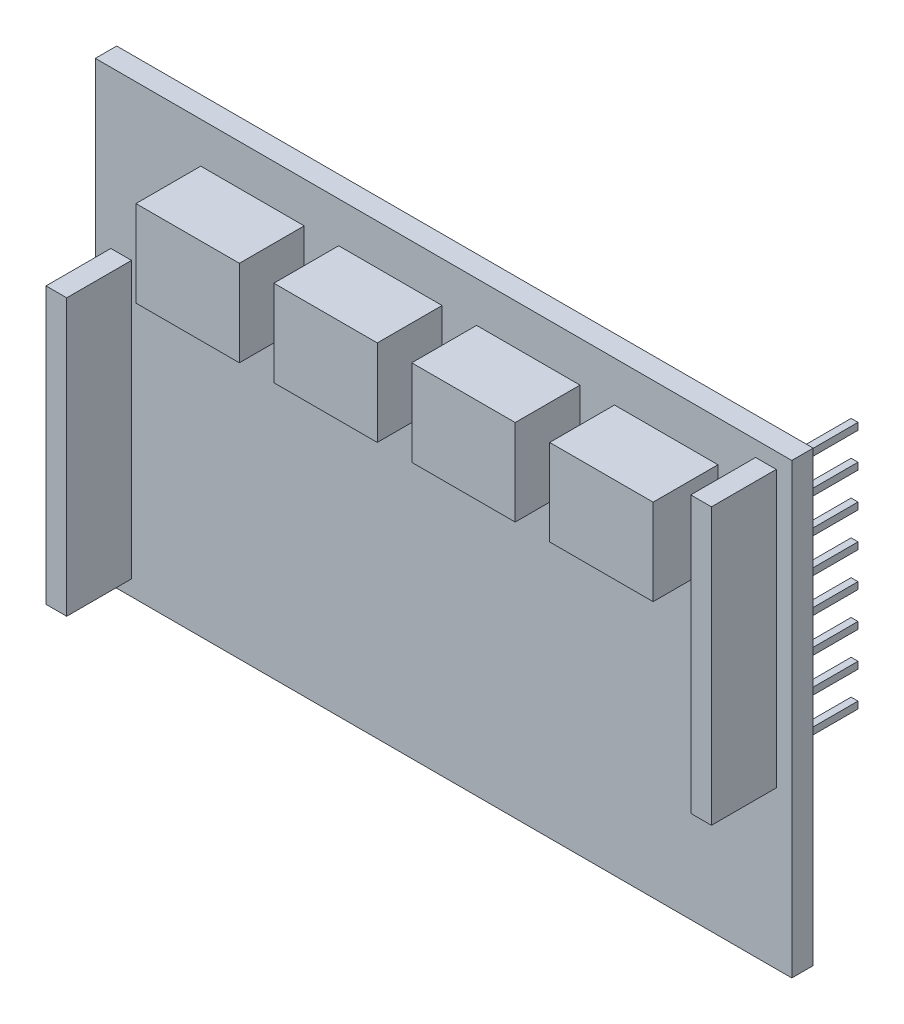
SolidWorks part; units mm, degrees
ref_plane "Front Plane" through (0, 0, 0) normal (0, 0, 1) x (1, 0, 0)
ref_plane "Top Plane" through (0, 0, 0) normal (0, 1, 0) x (1, 0, 0)
ref_plane "Right Plane" through (0, 0, 0) normal (1, 0, 0) x (0, 0, -1)
sketch "Sketch1" plane through (0, 0, 0) normal (0, 0, 1) x (1, 0, 0)
  line L0 (0, 0) -> (51.308, 0)
  line L1 (51.308, 0) -> (51.308, 33.02)
  line L2 (51.308, 33.02) -> (0, 33.02)
  line L3 (0, 33.02) -> (0, 0)
  dimension "D1" = 51.308
  dimension "D2" = 33.02
extrude "Boss-Extrude1" add sketch "Sketch1" along normal blind 1.5748
sketch "Sketch2" plane through (0, 0, 0) normal (0, 0, 1) x (1, 0, 0)
  line L0 (0, 33.02) -> (0, 0) construction
  line L1 (50.165, 31.877) -> (48.641, 31.877)
  line L2 (50.165, 31.877) -> (50.165, 11.557)
  line L3 (50.165, 11.557) -> (48.641, 11.557)
  line L4 (48.641, 31.877) -> (48.641, 11.557)
  line L5 (1.143, 1.143) -> (2.667, 1.143)
  line L6 (1.143, 1.143) -> (1.143, 21.463)
  line L7 (1.143, 21.463) -> (2.667, 21.463)
  line L8 (2.667, 1.143) -> (2.667, 21.463)
  line L9 (0, 0) -> (51.308, 0) construction
  line L10 (51.308, 0) -> (51.308, 33.02) construction
  line L11 (51.308, 33.02) -> (0, 33.02) construction
  dimension "D1" = 20.32
  dimension "D2" = 1.524
  dimension "D3" = 1.143
  dimension "D4" = 1.143
  dimension "D5" = 20.32
  dimension "D6" = 1.524
  dimension "D7" = 1.143
  dimension "D8" = 1.143
extrude "Boss-Extrude2" add sketch "Sketch2" along normal blind 6.35 contours L6 L5 L8 L7 | L2 L1 L4 L3
sketch "Sketch3" plane through (0, 0, 0) normal (0, 0, 1) x (1, 0, 0)
  line L1 (7.7673, 30.0262) -> (15.3873, 30.0262)
  line L2 (7.7673, 30.0262) -> (7.7673, 23.6762)
  line L3 (7.7673, 23.6762) -> (15.3873, 23.6762)
  line L4 (15.3873, 30.0262) -> (15.3873, 23.6762)
  dimension "D1" = 7.62
  dimension "D2" = 6.35
extrude "Boss-Extrude3" add sketch "Sketch3" along normal blind 6.35
pattern_linear "LPattern2" count 4 spacing 10.16 along (1, 0, 0) of "Boss-Extrude3"
sketch "Sketch5" plane through (0, 0, 0) normal (0, 0, -1) x (-1, 0, 0)
  line L0 (-51.308, 33.02) -> (0, 33.02) construction
  line L1 (-1.27, 1.27) -> (-2.794, 1.27)
  line L2 (-1.27, 1.27) -> (-1.27, 21.59)
  line L3 (-1.27, 21.59) -> (-2.794, 21.59)
  line L4 (-2.794, 1.27) -> (-2.794, 21.59)
  line L5 (-50.038, 31.75) -> (-48.514, 31.75)
  line L6 (-50.038, 31.75) -> (-50.038, 11.43)
  line L7 (-50.038, 11.43) -> (-48.514, 11.43)
  line L8 (-48.514, 31.75) -> (-48.514, 11.43)
  line L9 (-51.308, 0) -> (-51.308, 33.02) construction
  line L10 (0, 0) -> (-51.308, 0) construction
  line L11 (0, 33.02) -> (0, 0) construction
  dimension "D1" = 1.524
  dimension "D2" = 20.32
  dimension "D3" = 1.524
  dimension "D4" = 20.32
  dimension "D5" = 1.27
  dimension "D6" = 1.27
  dimension "D7" = 1.27
  dimension "D8" = 1.27
sketch "Sketch6" plane through (0, 0, 0) normal (0, 0, -1) x (-1, 0, 0)
  line L0 (-48.514, 31.75) -> (-48.514, 11.43) construction
  line L1 (-49.53, 31.2323) -> (-49.022, 31.2323)
  line L2 (-49.53, 31.2323) -> (-49.53, 30.7243)
  line L3 (-49.53, 30.7243) -> (-49.022, 30.7243)
  line L4 (-49.022, 31.2323) -> (-49.022, 30.7243)
  dimension "D1" = 0.508
  dimension "D2" = 0.508
  dimension "D3" = 0.508
extrude "Boss-Extrude4" add sketch "Sketch6" along normal blind 5.08
pattern_linear "LPattern3" count 8 spacing 2.54 along (0, -1, 0) of "Boss-Extrude4"
sketch "Sketch7" plane through (0, 0, 0) normal (0, 0, -1) x (-1, 0, 0)
  line L0 (-1.27, 1.27) -> (-1.27, 21.59) construction
  line L1 (-2.286, 1.778) -> (-1.778, 1.778)
  line L2 (-2.286, 1.778) -> (-2.286, 2.286)
  line L3 (-2.286, 2.286) -> (-1.778, 2.286)
  line L4 (-1.778, 1.778) -> (-1.778, 2.286)
  line L5 (-1.27, 1.27) -> (-2.794, 1.27) construction
  dimension "D1" = 0.508
  dimension "D2" = 0.508
  dimension "D3" = 0.508
extrude "Boss-Extrude5" add sketch "Sketch7" along normal blind 5.08
pattern_linear "LPattern4" count 8 spacing 2.54 along (0, 1, 0) of "Boss-Extrude5"
